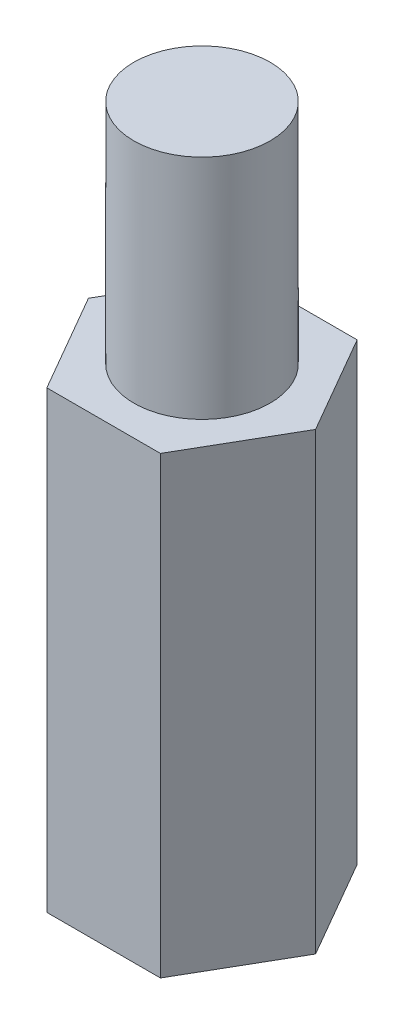
SolidWorks part; units mm, degrees
material "2.0402 (CuZn40Pb2)"
ref_plane "Front" through (0, 0, 0) normal (0, 0, 1) x (1, 0, 0)
ref_plane "Top" through (0, 0, 0) normal (0, 1, 0) x (1, 0, 0)
ref_plane "Right" through (0, 0, 0) normal (1, 0, 0) x (0, 0, -1)
sketch "Эскиз1" plane through (0, 0, 0) normal (0, 1, 0) x (1, 0, 0)
  line L1 (1.25, -2.1651) -> (2.5, 0)
  line L2 (2.5, 0) -> (1.25, 2.1651)
  line L3 (1.25, 2.1651) -> (-1.25, 2.1651)
  line L4 (-1.25, 2.1651) -> (-2.5, 0)
  line L5 (-2.5, 0) -> (-1.25, -2.1651)
  line L6 (-1.25, -2.1651) -> (1.25, -2.1651)
  circle A0 centre (0, 0) radius 2.1651 construction
  circle A1 centre (0, 0) radius 2.5 construction
  dimension "D1" = 5
  dimension "D2" = 2.5
extrude "Бобышка-Вытянуть1" add sketch "Эскиз1" along normal blind 10
sketch "Эскиз2" plane through (0, 10, 0) normal (0, 1, 0) x (1, 0, 0)
  circle A0 centre (0, 0) radius 1.5
  dimension "D1" = 3
extrude "Бобышка-Вытянуть2" add sketch "Эскиз2" along normal blind 5
sketch "Эскиз3" plane through (0, 0, 0) normal (0, -1, 0) x (1, 0, 0)
  circle A0 centre (0, 0) radius 1.5
  dimension "D1" = 3
extrude "Вырез-Вытянуть1" cut sketch "Эскиз3" against normal blind 10
